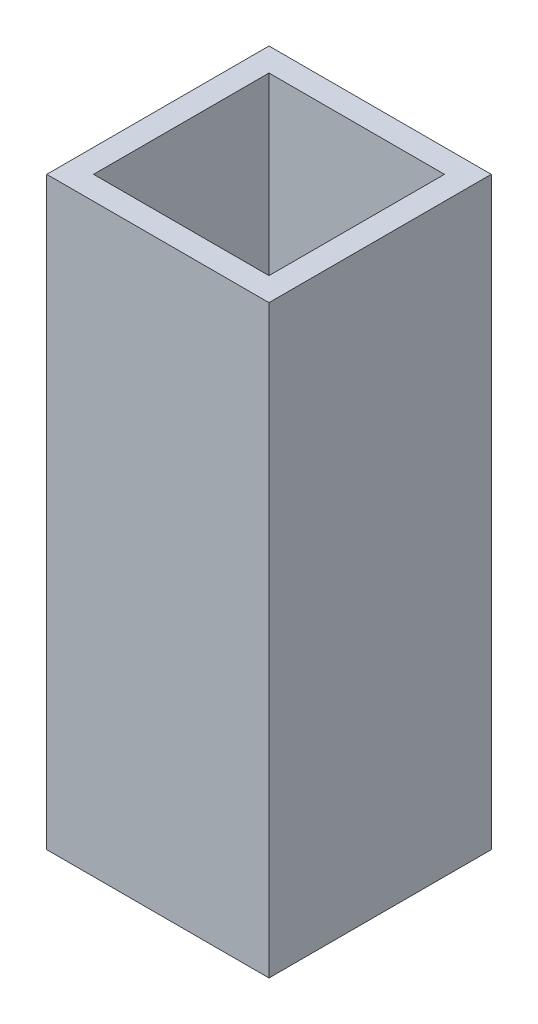
SolidWorks part; units mm, degrees
ref_plane "Front Plane" through (0, 0, 0) normal (0, 0, 1) x (1, 0, 0)
ref_plane "Top Plane" through (0, 0, 0) normal (0, 1, 0) x (1, 0, 0)
ref_plane "Right Plane" through (0, 0, 0) normal (1, 0, 0) x (0, 0, -1)
sketch "Sketch1" plane through (0, 0, 0) normal (0, 1, 0) x (1, 0, 0)
  line L1 (-9.5, -9.5) -> (9.5, -9.5)
  line L2 (-9.5, -9.5) -> (-9.5, 9.5)
  line L3 (-9.5, 9.5) -> (9.5, 9.5)
  line L4 (9.5, -9.5) -> (9.5, 9.5)
  line L5 (-9.5, -9.5) -> (9.5, 9.5) construction
  line L6 (-9.5, 9.5) -> (9.5, -9.5) construction
  point P0 (0, 0)
  dimension "D1" = 19
  dimension "D2" = 19
extrude "Extrude-Thin1" add sketch "Sketch1" along normal blind 50 thin thin type one direction reverse wall 2
